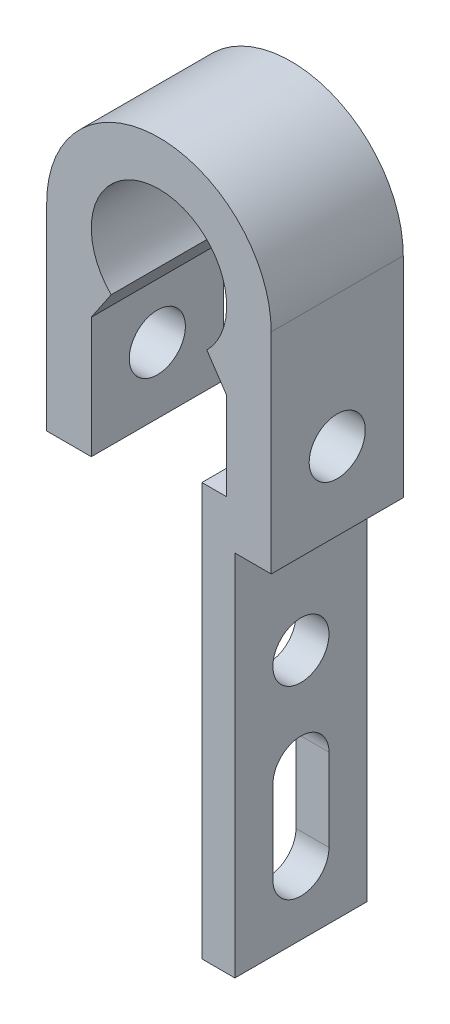
SolidWorks part; units mm, degrees
material "ABS"
ref_plane "Plano frontal" through (0, 0, 0) normal (0, 0, 1) x (1, 0, 0)
ref_plane "Plano superior" through (0, 0, 0) normal (0, 1, 0) x (1, 0, 0)
ref_plane "Plano direito" through (0, 0, 0) normal (1, 0, 0) x (0, 0, -1)
sketch "Esboço1" plane through (0, 0, 0) normal (0, 0, 1) x (1, 0, 0)
  line L0 (4.1, -4.6769) -> (2.8991, -2.8991)
  line L1 (4.1, -4.6769) -> (4.1, -10)
  line L2 (4.1, -10) -> (2.6, -10)
  line L3 (2.6, -10) -> (2.6, -35)
  line L4 (-6.8, -12) -> (-6.8, 0)
  line L5 (6.8, 0) -> (6.8, -12.7)
  line L6 (6.8, -12.7) -> (4.6, -12.7)
  line L7 (4.6, -12.7) -> (4.6, -35)
  line L8 (-6.8, -12) -> (-4.1, -12)
  line L9 (2.6, -35) -> (4.6, -35)
  line L10 (2.6, -10) -> (-3.7, -10) construction
  line L11 (-3.7, -10) -> (-3.7, -35) construction
  line L12 (-3.7, -35) -> (2.6, -35) construction
  line L13 (-4.1, -12) -> (-4.1, -4.6769)
  line L14 (-2.8991, -2.8991) -> (-4.1, -4.6769)
  arc A0 (-2.8991, -2.8991) -> (2.8991, -2.8991) centre (0, 0) cw
  arc A1 (-6.8, 0) -> (6.8, 0) centre (0, 0) cw
  dimension "D1" = 4.1
  dimension "D5" = 2.7
  dimension "D2" = 1.5
  dimension "D3" = 2
  dimension "D4" = 25
  dimension "D6" = 12
  dimension "D7" = 6.3
  dimension "D8" = 2.7
  dimension "D9" = 2
  dimension "D11" = 90
extrude "Ressalto-extrusão1" add sketch "Esboço1" along normal blind 8
sketch "Esboço2" plane through (-6.8, 0, 0) normal (-1, 0, 0) x (0, 0, 1)
  line L0 (4, -26) -> (4, -31) construction
  line L1 (5.7, -26) -> (5.7, -31)
  line L2 (2.3, -26) -> (2.3, -31)
  line L3 (8, -10) -> (0, -10) construction
  line L6 (8, -12) -> (0, -12) construction
  line L7 (0, 0) -> (0, -4.2) construction
  line L8 (0, 0) -> (0, -12) construction
  line L9 (0, -4.2) -> (8, -4.2) construction
  line L10 (8, 0) -> (8, -12) construction
  line L11 (8, -35) -> (0, -35) construction
  circle A0 centre (4, -8) radius 1.7
  circle A1 centre (4, -19.8) radius 1.7
  arc A2 (5.7, -26) -> (2.3, -26) centre (4, -26) ccw
  arc A3 (2.3, -31) -> (5.7, -31) centre (4, -31) ccw
  point P6 (4, -28.5)
  point P16 (4, -10)
  dimension "D1" = 7
  dimension "D2" = 3.4
  dimension "D3" = 5
  dimension "D4" = 4
  dimension "D5" = 4
  dimension "D6" = 4.2
extrude "Corte-extrusão1" cut sketch "Esboço2" against normal through all
